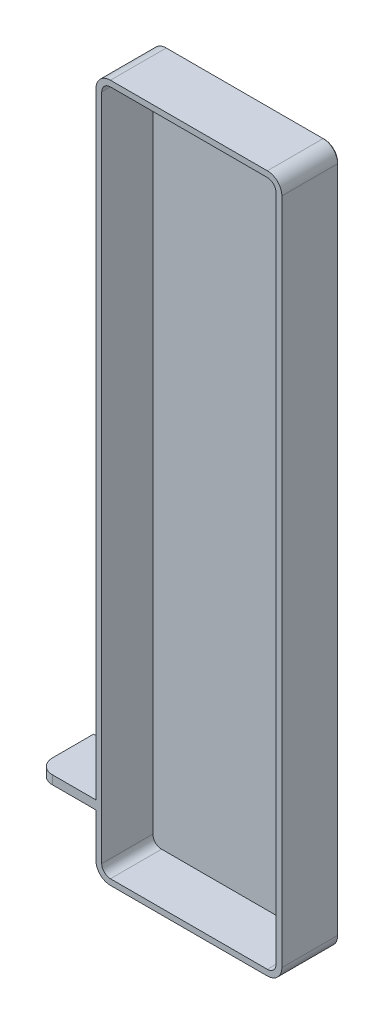
SolidWorks part; units mm, degrees
ref_plane "Front Plane" through (0, 0, 0) normal (0, 0, 1) x (1, 0, 0)
ref_plane "Top Plane" through (0, 0, 0) normal (0, 1, 0) x (1, 0, 0)
ref_plane "Right Plane" through (0, 0, 0) normal (1, 0, 0) x (0, 0, -1)
sketch "Sketch1" plane through (0, 0, 0) normal (0, 0, 1) x (1, 0, 0)
  line L1 (-86.7699, 240.5654) -> (-150.7699, 240.5654)
  line L2 (-86.7699, 240.5654) -> (-86.7699, 0.5654)
  line L3 (-86.7699, 0.5654) -> (-150.7699, 0.5654)
  line L4 (-150.7699, 240.5654) -> (-150.7699, 0.5654)
  dimension "D1" = 64
  dimension "D2" = 240
extrude "Boss-Extrude1" add sketch "Sketch1" along normal blind 19.6 separate body
fillet "Fillet1" radius 5 4 edges at (-150.7699, 0.5654, 9.8) (-86.7699, 0.5654, 9.8) (-86.7699, 240.5654, 9.8) (-150.7699, 240.5654, 9.8)
sketch "Sketch3" plane through (0, 0, 19.6) normal (0, 0, 1) x (1, 0, 0)
  line L9 (-148.7699, 235.5654) -> (-148.7699, 5.5654)
  line L10 (-145.7699, 2.5654) -> (-91.7699, 2.5654)
  line L11 (-88.7699, 5.5654) -> (-88.7699, 235.5654)
  line L12 (-91.7699, 238.5654) -> (-145.7699, 238.5654)
  line L13 (-148.7699, 235.5654) -> (-148.7699, 5.5654)
  line L14 (-145.7699, 2.5654) -> (-91.7699, 2.5654)
  line L15 (-88.7699, 5.5654) -> (-88.7699, 235.5654)
  line L16 (-91.7699, 238.5654) -> (-145.7699, 238.5654)
  arc A8 (-148.7699, 5.5654) -> (-145.7699, 2.5654) centre (-145.7699, 5.5654) ccw
  arc A9 (-91.7699, 2.5654) -> (-88.7699, 5.5654) centre (-91.7699, 5.5654) ccw
  arc A10 (-88.7699, 235.5654) -> (-91.7699, 238.5654) centre (-91.7699, 235.5654) ccw
  arc A11 (-145.7699, 238.5654) -> (-148.7699, 235.5654) centre (-145.7699, 235.5654) ccw
  arc A12 (-148.7699, 5.5654) -> (-145.7699, 2.5654) centre (-145.7699, 5.5654) ccw
  arc A13 (-91.7699, 2.5654) -> (-88.7699, 5.5654) centre (-91.7699, 5.5654) ccw
  arc A14 (-88.7699, 235.5654) -> (-91.7699, 238.5654) centre (-91.7699, 235.5654) ccw
  arc A15 (-145.7699, 238.5654) -> (-148.7699, 235.5654) centre (-145.7699, 235.5654) ccw
  dimension "D1" = 2
extrude "Cut-Extrude1" cut sketch "Sketch3" against normal offset from surface (17.6 mm away) 2 up to face at (-118.7699, 120.5654, 0)
sketch "Sketch4" plane through (-150.7699, 0, 0) normal (-1, 0, 0) x (0, 0, 1)
  line L0 (0, 235.5654) -> (0, 5.5654) construction
  line L1 (0, 23.5654) -> (19.6, 23.5654)
  line L2 (0, 23.5654) -> (0, 20.5654)
  line L3 (0, 20.5654) -> (19.6, 20.5654)
  line L4 (19.6, 23.5654) -> (19.6, 20.5654)
  line L5 (19.6, 235.5654) -> (19.6, 5.5654) construction
  line L6 (19.6, 0.5654) -> (0, 0.5654) construction
  dimension "D1" = 3
  dimension "D2" = 20
extrude "Boss-Extrude2" add sketch "Sketch4" along normal blind 20
fillet "Fillet2" radius 5 1 edges at (-170.7699, 22.0654, 19.6)
move or copy body "Body-Move/Copy1" bodies to move or copy 104 copy no translate (0, -0.5654, 0) parameters "D1"=0, "D2"=0.5654, "D3"=0
move or copy body "Body-Move/Copy2" bodies to move or copy 105 copy no translate (150.7699, 0, 0) parameters "D1"=150.7699, "D2"=0, "D3"=0
chamfer "Chamfer1" distance 0.4 12 edges at (62.5355, 1.4645, 0) (64, 120, 0) (62.5355, 238.5355, 0) (32, 240, 0) (1.4645, 238.5355, 0) (0, 129, 0) (-10, 23, 0) (-20, 21.5, 0) (-10, 20, 0) (0, 12.5, 0) (1.4645, 1.4645, 0) (32, 0, 0)
